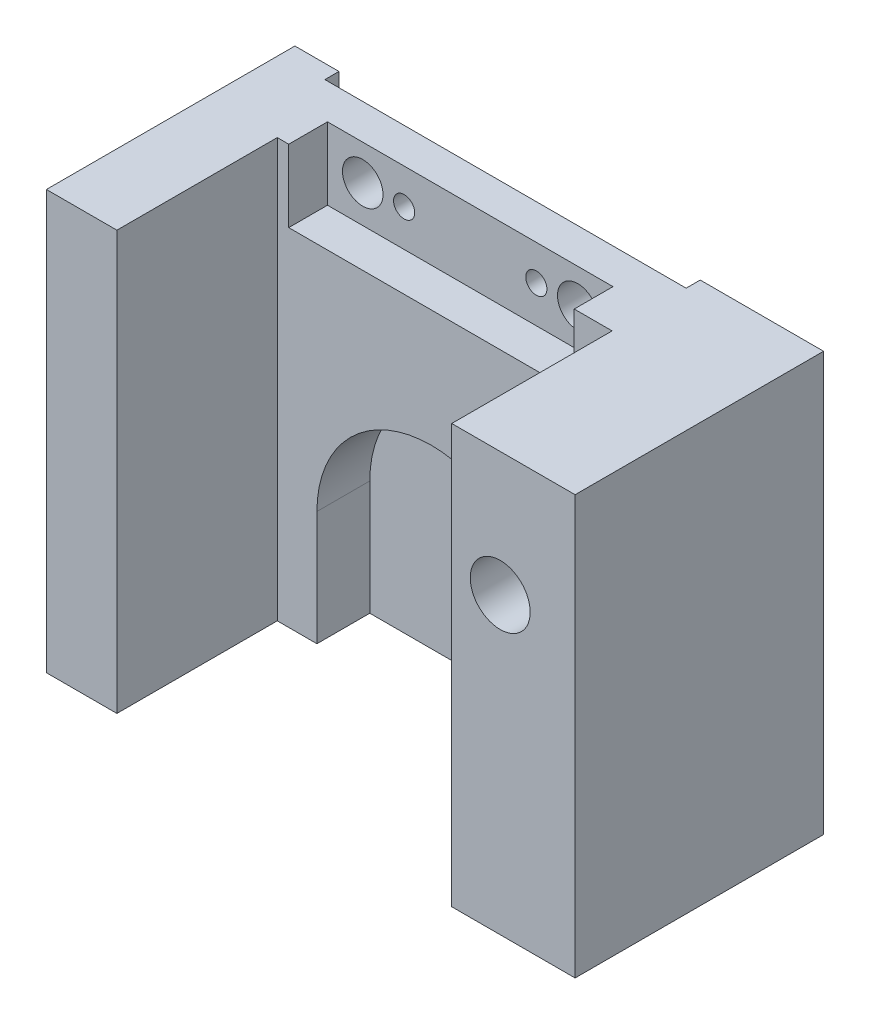
SolidWorks part; units mm, degrees
ref_plane "前视基准面" through (0, 0, 0) normal (0, 0, 1) x (1, 0, 0)
ref_plane "上视基准面" through (0, 0, 0) normal (0, 1, 0) x (1, 0, 0)
ref_plane "右视基准面" through (0, 0, 0) normal (1, 0, 0) x (0, 0, -1)
sketch "草图1" plane through (0, 0, 0) normal (0, 0, 1) x (1, 0, 0)
  line L1 (-7.5503, 16.7364) -> (22.4497, 16.7364)
  line L2 (-7.5503, 16.7364) -> (-7.5503, -11.2636)
  line L3 (-7.5503, -11.2636) -> (22.4497, -11.2636)
  line L4 (22.4497, 16.7364) -> (22.4497, -11.2636)
  dimension "D1" = 30
  dimension "D2" = 28
extrude "凸台-拉伸1" add sketch "草图1" along normal blind 10
sketch "草图2" plane through (0, 0, 0) normal (0, 0, -1) x (-1, 0, 0)
  line L0 (-22.4497, 16.7364) -> (7.5503, 16.7364) construction
  line L1 (7.5503, 16.7364) -> (7.5503, -11.2636) construction
  line L3 (5.0503, 16.7364) -> (-15.4497, 16.7364)
  line L4 (5.0503, 16.7364) -> (5.0503, 3.7364)
  line L5 (2.0503, 0.7364) -> (-12.4497, 0.7364)
  line L6 (-15.4497, 16.7364) -> (-15.4497, 3.7364)
  arc A0 (2.0503, 0.7364) -> (5.0503, 3.7364) centre (2.0503, 3.7364) ccw
  arc A1 (-12.4497, 0.7364) -> (-15.4497, 3.7364) centre (-12.4497, 3.7364) cw
  point P0 (5.0503, 16.7364)
  point P11 (5.0503, 0.7364)
  dimension "D4" = 3
  dimension "D1" = 2.5
  dimension "D2" = 20.5
  dimension "D3" = 16
extrude "切除-拉伸2" cut sketch "草图2" against normal blind 0.8
sketch "草图3" plane through (0, 0, 0.8) normal (0, 0, -1) x (-1, 0, 0)
  line L0 (5.0503, 16.7364) -> (-15.4497, 16.7364) construction
  line L2 (-15.1997, 16.7364) -> (4.8003, 16.7364)
  line L3 (-15.1997, 16.7364) -> (-15.1997, 3.7364)
  line L4 (-12.1997, 0.7364) -> (1.8003, 0.7364)
  line L5 (4.8003, 16.7364) -> (4.8003, 3.7364)
  arc A0 (1.8003, 0.7364) -> (4.8003, 3.7364) centre (1.8003, 3.7364) ccw
  arc A1 (-12.1997, 0.7364) -> (-15.1997, 3.7364) centre (-12.1997, 3.7364) cw
  point P0 (-5.1997, 16.7364)
  point P9 (4.8003, 0.7364)
  point P12 (1.8003, 10.7364)
  point P14 (-12.1997, 10.7364)
  dimension "D4" = 3
  dimension "D1" = 20
  dimension "D2" = 10
  dimension "D3" = 16
  dimension "D5" = 6
  dimension "D6" = 6
  dimension "D7" = 3
  dimension "D8" = 3
hole_wizard "M1.4x0.3 螺纹孔2" positions "草图9" profile "草图7" tap size "M1.4x0.3" standard "ANSI Metric"
sketch "草图9" plane through (0, 0, 0.8) normal (0, 0, -1) x (-1, 0, 0)
  line L0 (-15.1997, 16.7364) -> (4.8003, 16.7364) construction
  point P0 (-12.1997, 8.7364)
  point P3 (1.8003, 8.7364)
  dimension "D1" = 8
  dimension "D2" = 8
sketch "草图7" plane through (12.1997, 8.7364, 0.8) normal (1, 0, 0) x (0, 1, 0)
  line L0 (0, 0) -> (0, 4.0305)
  line L1 (0, 4.0305) -> (0.55, 3.7)
  line L2 (0.55, 3.7) -> (0.55, 0)
  line L5 (0.55, 0) -> (0, 0)
  line L10 (0, 4.0305) -> (-0.55, 3.7) construction
  line L11 (0, -6.35) -> (0, 107.95) construction
  dimension "螺纹孔钻头直径" = 1.1
  dimension "螺纹孔钻头深度" = 3.7
  dimension "导头角度" = 118
cosmetic thread "孔螺蚊线9" parameters "D1"=3.5, "D2"=1.4
cosmetic thread "孔螺蚊线10" parameters "D1"=3.5, "D2"=1.4
sketch "草图10" plane through (0, 16.7364, 0) normal (0, 1, 0) x (1, 0, 0)
  line L0 (22.4497, -0.8) -> (-7.5503, -0.8)
  line L1 (22.4497, -10) -> (22.4497, 0) construction
  line L2 (-7.5503, -10) -> (-7.5503, 0) construction
  line L3 (22.4497, 0) -> (15.4497, 0) construction
  point P8 (5.1997, -0.8)
  dimension "D1" = 0.8
  dimension "D8" = 12.75
sketch "草图11" plane through (0, 0, 0) normal (0, 0, -1) x (-1, 0, 0)
  line L0 (-12.1997, 0.7364) -> (1.8003, 0.7364) construction
  line L1 (-7.5497, -2.0636) -> (-2.8497, -2.0636)
  line L2 (-7.7997, 0.7364) -> (-2.5997, 0.7364)
  line L3 (-7.7997, 0.7364) -> (-7.7997, -1.8136)
  line L5 (-2.5997, 0.7364) -> (-2.5997, -1.8136)
  arc A0 (-2.8497, -2.0636) -> (-2.5997, -1.8136) centre (-2.5997, -2.0636) ccw
  arc A1 (-7.7997, -1.8136) -> (-7.5497, -2.0636) centre (-7.7997, -2.0636) ccw
  point P0 (-5.1997, 0.7364)
  dimension "D4" = 2.8
  dimension "D5" = 0.5
  dimension "D6" = 0.5
  dimension "D1" = 5.2
  dimension "D2" = 2.6
  dimension "D3" = 2.8
  dimension "D7" = 2.8
  dimension "D8" = 2.8
  dimension "D9" = 4.7
extrude "切除-拉伸4" cut sketch "草图11" against normal blind 0.5
sketch "草图12" plane through (0, 0, 0) normal (0, 0, -1) x (-1, 0, 0)
  line L0 (-22.4497, -11.2636) -> (-22.4497, 16.7364) construction
  line L1 (7.5503, -11.2636) -> (-22.4497, -11.2636)
  line L2 (7.5503, -11.2636) -> (7.5503, -7.0136)
  line L3 (7.5503, -7.0136) -> (-22.4497, -7.0136)
  line L4 (-22.4497, -11.2636) -> (-22.4497, -7.0136)
  dimension "D1" = 4.25
extrude "切除-拉伸5" cut sketch "草图12" against normal blind 10
sketch "草图13" plane through (0, 0, 0) normal (0, 0, -1) x (-1, 0, 0)
  line L1 (-7.5497, -2.0636) -> (-2.8497, -2.0636) construction
  line L3 (-7.5497, -2.0636) -> (-2.8497, -2.0636) construction
  circle A0 centre (-18.1997, 9.6864) radius 1.7
  point P0 (-18.1997, 9.6864)
  point P6 (-5.1997, -2.0636)
  dimension "D3" = 3.4
  dimension "D1" = 13
  dimension "D2" = 11.75
extrude "切除-拉伸6" cut sketch "草图13" against normal blind 10
sketch "草图14" plane through (0, 0, 10) normal (0, 0, 1) x (1, 0, 0)
  line L0 (-7.5503, -7.0136) -> (22.4497, -7.0136) construction
  line L1 (-7.5503, 16.7364) -> (15.4497, 16.7364)
  line L2 (-7.5503, 16.7364) -> (-7.5503, -7.0136)
  line L3 (-7.5503, -7.0136) -> (15.4497, -7.0136)
  line L4 (15.4497, 16.7364) -> (15.4497, -7.0136)
  line L5 (22.4497, -7.0136) -> (22.4497, 16.7364) construction
  dimension "D1" = 7
extrude "切除-拉伸7" cut sketch "草图14" against normal blind 5
sketch "草图16" plane through (0, 0, 5) normal (0, 0, 1) x (1, 0, 0)
  line L2 (-7.5503, -7.0136) -> (15.4497, -7.0136) construction
  line L3 (-7.5503, 16.7364) -> (-7.5503, -7.0136) construction
  line L5 (-1.3003, -7.0136) -> (11.6997, -7.0136)
  line L7 (-1.3003, -7.0136) -> (-1.3003, -0.5136)
  line L9 (11.6997, -7.0136) -> (11.6997, -0.5136)
  arc A0 (11.6997, -0.5136) -> (-1.3003, -0.5136) centre (5.1997, -0.5136) ccw
  point P0 (5.1997, -7.0136)
  dimension "D4" = 6.5
  dimension "D5" = 6.5
  dimension "D1" = 12.75
  dimension "D2" = 13
  dimension "D3" = 6.5
sketch "草图17" plane through (0, 0, 0.5) normal (0, 0, -1) x (-1, 0, 0)
  line L0 (-2.5997, 0.7364) -> (-7.7997, 0.7364) construction
  line L3 (1.3003, -7.0136) -> (-11.6997, -7.0136) construction
  point P0 (-5.1997, 0.7364)
  point P1 (-5.1997, -0.5136)
  dimension "D1" = 6.5
extrude "切除-拉伸9" cut sketch "草图16" against normal blind 3
sketch "草图20" plane through (0, 0, 10) normal (0, 0, 1) x (1, 0, 0)
  line L1 (15.4497, 16.7364) -> (22.4497, 16.7364)
  line L2 (15.4497, 16.7364) -> (15.4497, -7.0136)
  line L3 (15.4497, -7.0136) -> (22.4497, -7.0136)
  line L4 (22.4497, 16.7364) -> (22.4497, -7.0136)
  circle A0 centre (18.1997, 9.6864) radius 1.7
  dimension "D1" = 3.4
extrude "凸台-拉伸3" add sketch "草图20" along normal blind 4.1
sketch "草图21" plane through (0, 0, 0.8) normal (0, 0, -1) x (-1, 0, 0)
  point P0 (-5.1997, 16.7364)
sketch "草图22" plane through (0, 16.7364, 0) normal (0, 1, 0) x (1, 0, 0)
  line L0 (5.1997, -0.8) -> (5.1997, -5)
  line L1 (15.4497, -5) -> (-7.5503, -5) construction
sketch "草图23" plane through (0, 0, 5) normal (0, 0, 1) x (1, 0, 0)
  line L0 (-7.5503, -7.0136) -> (-1.3003, -7.0136) construction
  line L1 (-7.5503, 16.7364) -> (-3.5503, 16.7364)
  line L2 (-7.5503, 16.7364) -> (-7.5503, -7.0136)
  line L3 (-7.5503, -7.0136) -> (-3.5503, -7.0136)
  line L4 (-3.5503, 16.7364) -> (-3.5503, -7.0136)
  dimension "D1" = 4
extrude "凸台-拉伸4" add sketch "草图23" along normal blind 9.1
sketch "草图24" plane through (0, 0, 0.8) normal (0, 0, -1) x (-1, 0, 0)
  line L0 (-15.1997, 16.7364) -> (4.8003, 16.7364) construction
  line L2 (2.9003, 16.7364) -> (-13.2997, 16.7364)
  line L3 (2.9003, 16.7364) -> (2.9003, 12.6364)
  line L4 (2.9003, 12.6364) -> (-13.2997, 12.6364)
  line L5 (-13.2997, 16.7364) -> (-13.2997, 12.6364)
  dimension "D1" = 16.2
  dimension "D2" = 8.1
  dimension "D3" = 4.1
  dimension "D4" = 0
extrude "切除-拉伸10" cut sketch "草图24" against normal blind 5
sketch "草图25" plane through (0, 0, 5) normal (0, 0, 1) x (1, 0, 0)
  line L0 (-3.5503, -7.0136) -> (-3.5503, 16.7364) construction
  line L1 (15.4497, 16.7364) -> (-3.5503, 16.7364)
  line L2 (15.4497, 16.7364) -> (15.4497, 10.7364)
  line L3 (15.4497, 10.7364) -> (-3.5503, 10.7364)
  line L4 (-3.5503, 16.7364) -> (-3.5503, 10.7364)
  dimension "D1" = 6
sketch "草图29" plane through (0, 12.6364, 0) normal (0, 1, 0) x (1, 0, 0)
  line L0 (13.2997, -5) -> (13.2997, -0.8) construction
  line L1 (-2.9003, -0.8) -> (13.2997, -0.8)
  line L2 (-2.9003, -0.8) -> (-2.9003, -2.8)
  line L3 (-2.9003, -2.8) -> (13.2997, -2.8)
  line L4 (13.2997, -0.8) -> (13.2997, -2.8)
  dimension "D1" = 2
extrude "凸台-拉伸5" add sketch "草图29" along normal blind 4.1
sketch "草图30" plane through (0, 0, 0.8) normal (0, 0, -1) x (-1, 0, 0)
  line L0 (-15.1997, 16.7364) -> (4.8003, 16.7364) construction
  circle A0 centre (0.9003, 14.7364) radius 1.15
  circle A1 centre (-11.2997, 14.7364) radius 1.15
  circle A3 centre (-1.4497, 14.7364) radius 0.6
  circle A4 centre (-8.9497, 14.7364) radius 0.6
  dimension "D1" = 2.3
  dimension "D2" = 2.3
  dimension "D7" = 1.2
  dimension "D8" = 1.2
  dimension "D3" = 2
  dimension "D4" = 2
  dimension "D5" = 6.1
  dimension "D6" = 6.1
  dimension "D9" = 2
  dimension "D10" = 2
  dimension "D11" = 3.75
  dimension "D12" = 3.75
extrude "切除-拉伸12" cut sketch "草图30" against normal blind 5
